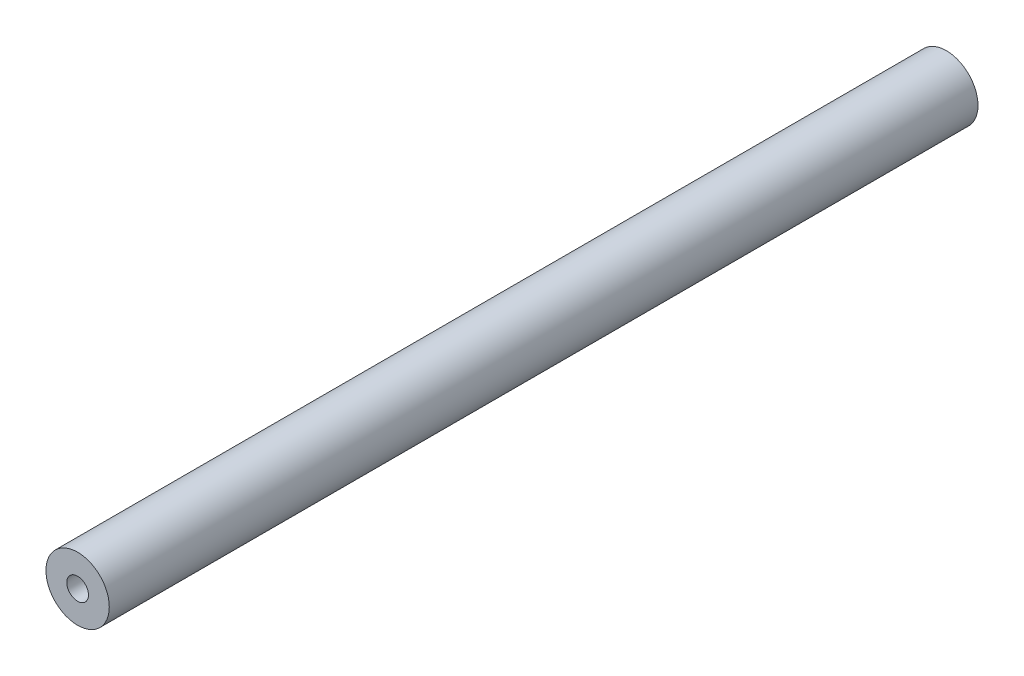
SolidWorks part; units mm, degrees
ref_plane "Front Plane" through (0, 0, 0) normal (0, 0, 1) x (1, 0, 0)
ref_plane "Top Plane" through (0, 0, 0) normal (0, 1, 0) x (1, 0, 0)
ref_plane "Right Plane" through (0, 0, 0) normal (1, 0, 0) x (0, 0, -1)
sketch "Sketch1" plane through (0, 0, 0) normal (0, 0, 1) x (1, 0, 0)
  circle A0 centre (0, 0) radius 8.75
extrude "Boss-Extrude1" add sketch "Sketch1" along normal blind 240
sketch "Sketch2" plane through (0, 0, 0) normal (0, 0, 1) x (1, 0, 0)
  circle A0 centre (0, 0) radius 3
extrude "Cut-Extrude2" cut sketch "Sketch2" along normal blind 276
